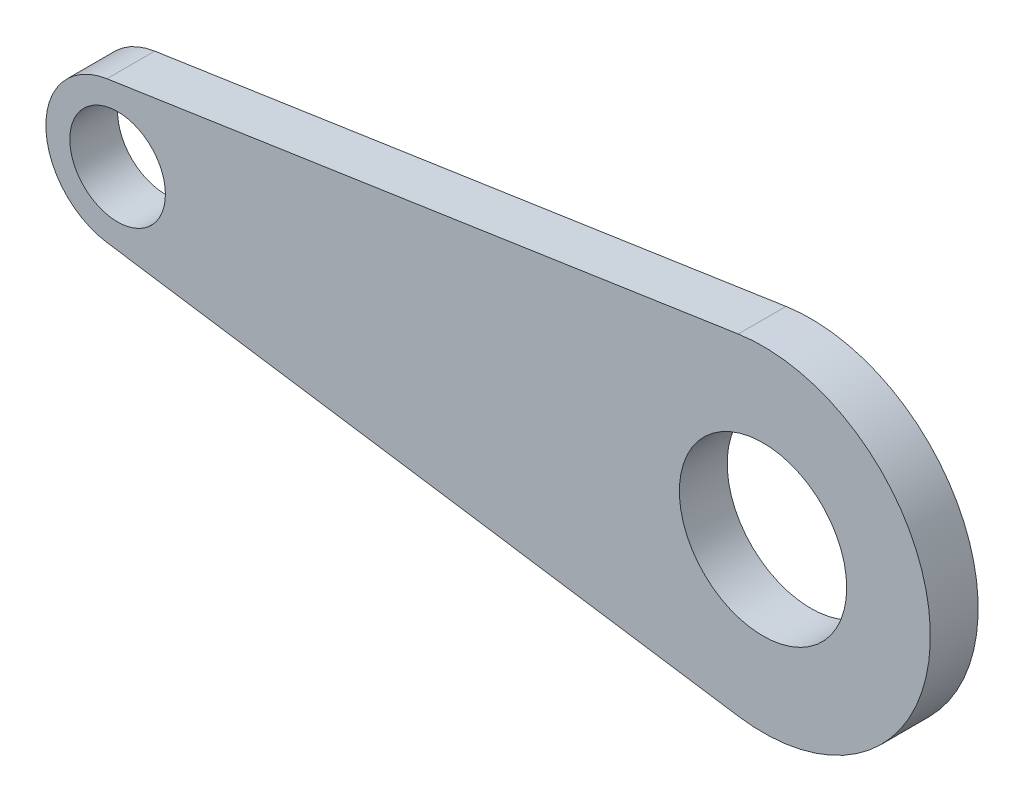
SolidWorks part; units mm, degrees
ref_plane "Спереди" through (0, 0, 0) normal (0, 0, 1) x (1, 0, 0)
ref_plane "Сверху" through (0, 0, 0) normal (0, 1, 0) x (1, 0, 0)
ref_plane "Справа" through (0, 0, 0) normal (1, 0, 0) x (0, 0, -1)
sketch "Эскиз1" plane through (0, 0, 0) normal (0, 0, 1) x (1, 0, 0)
  line L0 (-0.2222, 1.4834) -> (12.9815, 3.4614)
  line L1 (-0.2222, -1.4834) -> (12.9815, -3.4614)
  arc A0 (12.9815, -3.4614) -> (12.9815, 3.4614) centre (13.5, 0) ccw
  arc A1 (-0.2222, 1.4834) -> (-0.2222, -1.4834) centre (0, 0) ccw
  circle A2 centre (0, 0) radius 1
  circle A4 centre (13.5, 0) radius 1.75
  dimension "D1" = 7
  dimension "D2" = 3
  dimension "D4" = 3.5
  dimension "D5" = 2
  dimension "D3" = 13.5
extrude "Пластина" add sketch "Эскиз1" along normal blind 1
